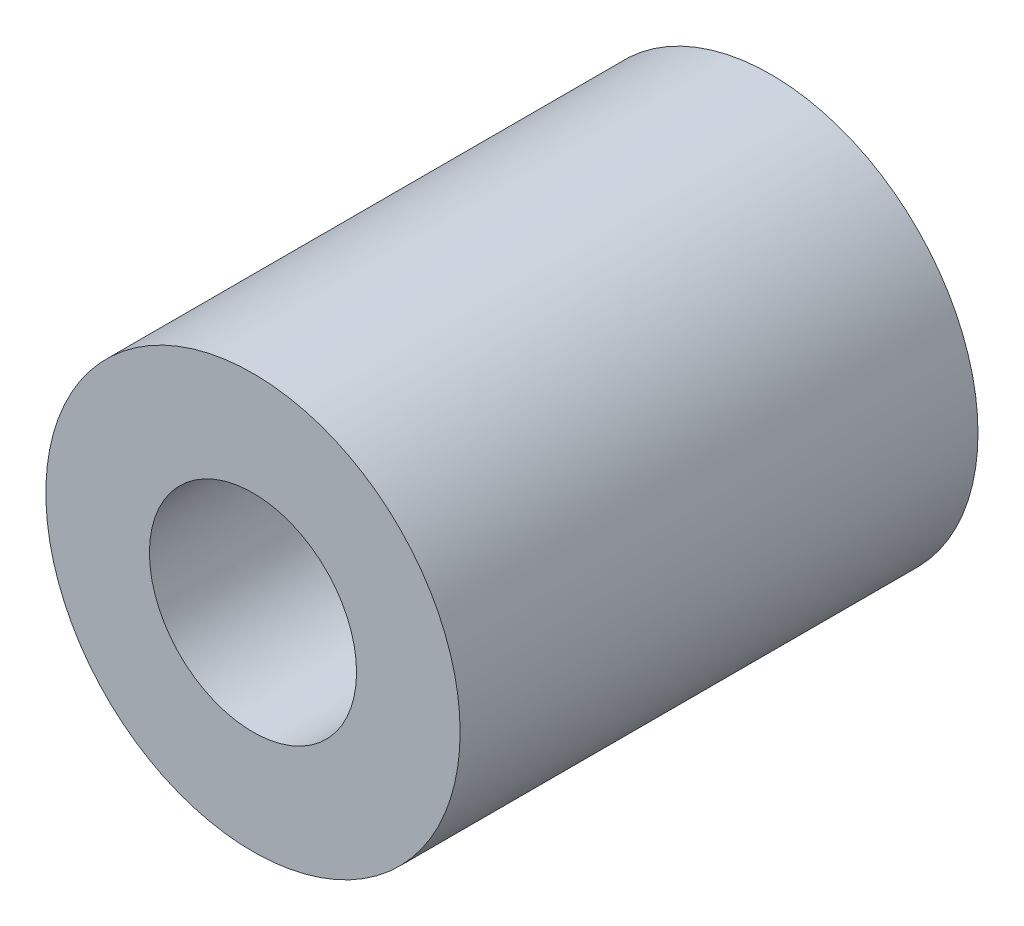
SolidWorks part; units mm, degrees
ref_plane "前视基准面" through (0, 0, 0) normal (0, 0, 1) x (1, 0, 0)
ref_plane "上视基准面" through (0, 0, 0) normal (0, 1, 0) x (1, 0, 0)
ref_plane "右视基准面" through (0, 0, 0) normal (1, 0, 0) x (0, 0, -1)
sketch "草图1" plane through (0, 0, 0) normal (0, 0, 1) x (1, 0, 0)
  circle A0 centre (0, 0) radius 4
  circle A1 centre (0, 0) radius 2
  dimension "D1" = 8
  dimension "D2" = 4
extrude "凸台-拉伸1" add sketch "草图1" along normal mid plane 10
